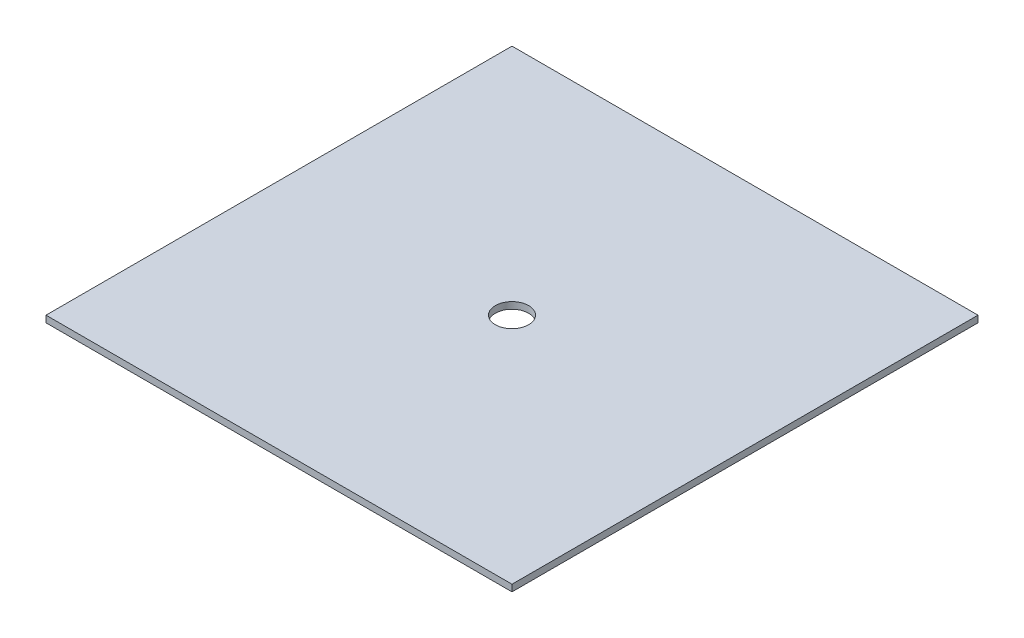
SolidWorks part; units mm, degrees
ref_plane "Front Plane" through (0, 0, 0) normal (0, 0, 1) x (1, 0, 0)
ref_plane "Top Plane" through (0, 0, 0) normal (0, 1, 0) x (1, 0, 0)
ref_plane "Right Plane" through (0, 0, 0) normal (1, 0, 0) x (0, 0, -1)
sketch "Sketch6" plane through (0, 0, 0) normal (0, 1, 0) x (1, 0, 0)
  line L1 (-175, 175) -> (175, 175)
  line L2 (-175, 175) -> (-175, -175)
  line L3 (-175, -175) -> (175, -175)
  line L4 (175, 175) -> (175, -175)
  line L5 (-175, 175) -> (175, -175) construction
  line L6 (-175, -175) -> (175, 175) construction
  circle A0 centre (0, 0) radius 12.5
extrude "Boss-Extrude1" add sketch "Sketch6" along normal blind 5
